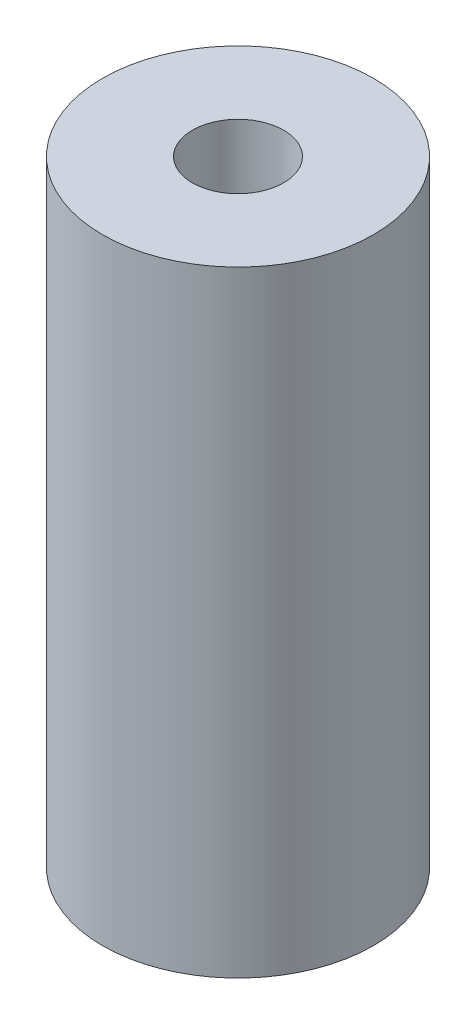
SolidWorks part; units mm, degrees
ref_plane "Front Plane" through (0, 0, 0) normal (0, 0, 1) x (1, 0, 0)
ref_plane "Top Plane" through (0, 0, 0) normal (0, 1, 0) x (1, 0, 0)
ref_plane "Right Plane" through (0, 0, 0) normal (1, 0, 0) x (0, 0, -1)
sketch "Sketch1" plane through (0, 0, 0) normal (0, 1, 0) x (1, 0, 0)
  circle A0 centre (0, 0) radius 23.749
  circle A1 centre (0, 0) radius 8.001
  dimension "D1" = 47.498
  dimension "D2" = 16.002
extrude "Boss-Extrude1" add sketch "Sketch1" along normal blind 107.95
